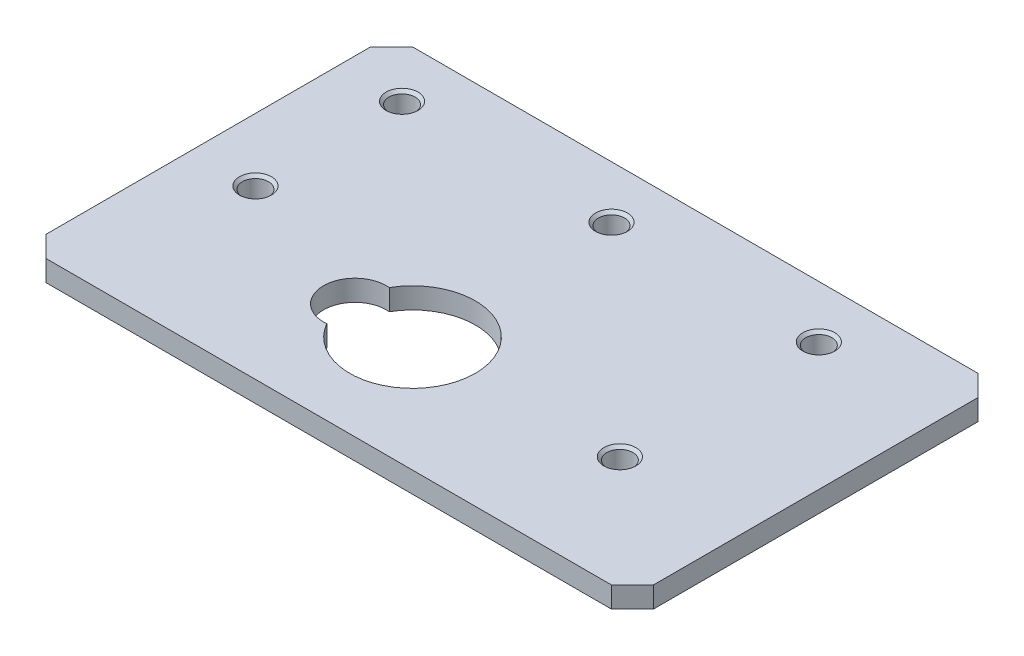
SolidWorks part; units mm, degrees
ref_plane "Front Plane" through (0, 0, 0) normal (0, 0, 1) x (1, 0, 0)
ref_plane "Top Plane" through (0, 0, 0) normal (0, 1, 0) x (1, 0, 0)
ref_plane "Right Plane" through (0, 0, 0) normal (1, 0, 0) x (0, 0, -1)
sketch "Sketch1" plane through (0, 0, 0) normal (0, 1, 0) x (1, 0, 0)
  line L1 (-29, -17.5) -> (29, -17.5)
  line L2 (-29, -17.5) -> (-29, 17.5)
  line L3 (-29, 17.5) -> (29, 17.5)
  line L4 (29, -17.5) -> (29, 17.5)
  line L5 (-29, -17.5) -> (29, 17.5) construction
  line L6 (-29, 17.5) -> (29, -17.5) construction
  point P0 (0, 0)
  dimension "D1" = 35
  dimension "D2" = 58
extrude "Boss-Extrude1" add sketch "Sketch1" along normal blind 2
hole_wizard "M3x0.5 Tapped Hole1" positions "Sketch2" profile "Sketch3" tap size "M3x0.5" standard "JIS" end condition through all
sketch "Sketch2" plane through (0, 2, 0) normal (0, 1, 0) x (1, 0, 0)
  line L0 (-29, -17.5) -> (29, -17.5) construction
  line L1 (29, -17.5) -> (29, 17.5) construction
  point P0 (-23, 12.5)
  point P2 (-3, 12.5)
  point P4 (16.8, 12.5)
  point P6 (16.8, -6.5)
  point P8 (-23, -1.5)
  point P15 (0, 0)
  point P16 (0, 0)
  dimension "D1" = 16
  dimension "D2" = 12.2
  dimension "D3" = 19.8
  dimension "D4" = 20
  dimension "D5" = 19
  dimension "D6" = 11
sketch "Sketch3" plane through (-23, 2, -12.5) normal (1, 0, 0) x (0, 0, 1)
  line L0 (0, 0) -> (0, 2)
  line L1 (0, 2) -> (1.25, 2)
  line L2 (1.25, 2) -> (1.25, 0.275)
  line L3 (1.25, 0.275) -> (1.525, 0)
  line L5 (1.525, 0) -> (0, 0)
  line L6 (-1.25, 0.275) -> (-1.525, 0) construction
  line L11 (0, -6.35) -> (0, 107.95) construction
  dimension "Thru Tap Drill Dia." = 2.5
  dimension "Thru Tap Drill Depth" = 2
  dimension "Near C'Sink Dia." = 3.05
  dimension "Near C'Sink Angle" = 90
cosmetic thread "Hole Thread1" parameters "D2"=3
cosmetic thread "Hole Thread2" parameters "D2"=3
cosmetic thread "Hole Thread3" parameters "D2"=3
cosmetic thread "Hole Thread4" parameters "D2"=3
cosmetic thread "Hole Thread5" parameters "D2"=3
sketch "Sketch4" plane through (0, 2, 0) normal (0, 1, 0) x (1, 0, 0)
  line L0 (-29, 17.5) -> (-29, -17.5) construction
  line L1 (-29, -17.5) -> (29, -17.5) construction
  arc A0 (-8.2045, -3.5146) -> (-8.2045, -9.4854) centre (-8.5, -6.5) ccw
  arc A1 (-8.2045, -9.4854) -> (-8.2045, -3.5146) centre (-3, -6.5) ccw
  dimension "D1" = 6
  dimension "D2" = 12
  dimension "D3" = 5.5
  dimension "D4" = 26
  dimension "D5" = 11
extrude "Cut-Extrude1" cut sketch "Sketch4" against normal through all
chamfer "Chamfer1" distance 2 angle 45 4 edges at (-29, 1, -17.5) (-29, 1, 17.5) (29, 1, -17.5) (29, 1, 17.5)
